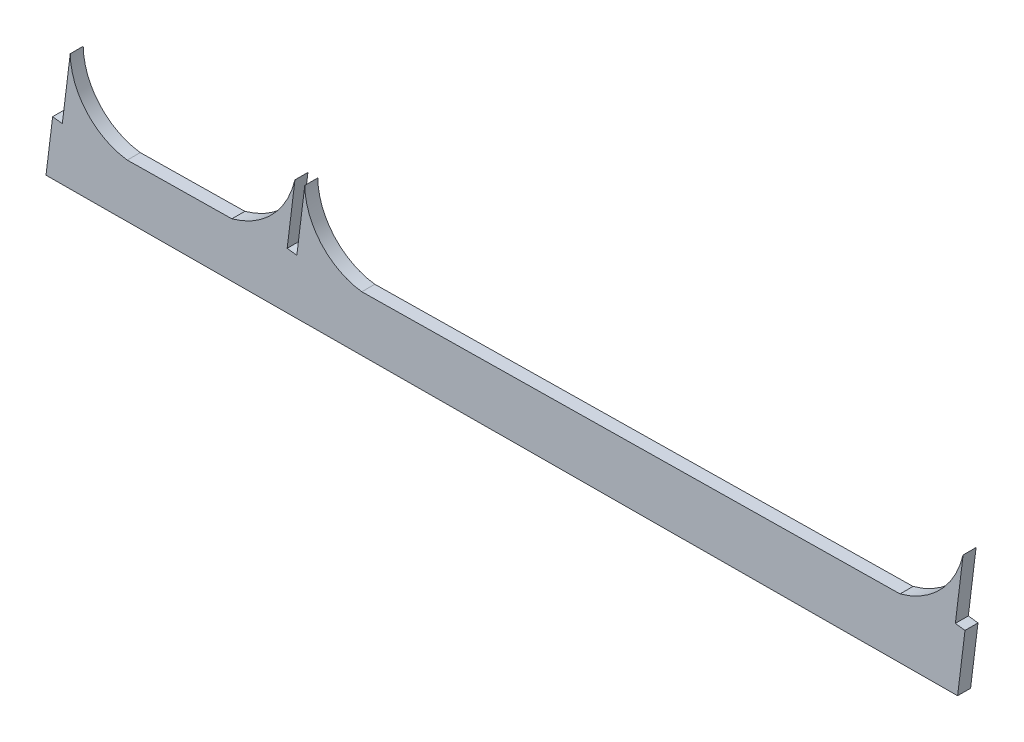
SolidWorks part; units mm, degrees
ref_plane "前视基准面" through (0, 0, 0) normal (0, 0, 1) x (1, 0, 0)
ref_plane "上视基准面" through (0, 0, 0) normal (0, 1, 0) x (1, 0, 0)
ref_plane "右视基准面" through (0, 0, 0) normal (1, 0, 0) x (0, 0, -1)
sketch "Model" plane through (0, 0, 0) normal (0, 0, 1) x (1, 0, 0)
  line L0 (13.7561, 8.5046) -> (154.0853, 9.2705)
  line L1 (16.2661, 16.6383) -> (14.7773, 16.8211)
  line L2 (52.3707, 17.1371) -> (50.8818, 17.32)
  line L3 (155.2257, 18.5582) -> (153.7369, 18.741)
  line L4 (14.7773, 16.8211) -> (13.7561, 8.5046)
  line L5 (17.4848, 26.5638) -> (16.2661, 16.6383)
  line L6 (26.2651, 16.7765) -> (42.3716, 16.999)
  line L7 (52.0755, 27.0417) -> (50.8818, 17.32)
  line L8 (53.5894, 27.0626) -> (52.3707, 17.1371)
  line L9 (62.3697, 17.2753) -> (145.2266, 18.4201)
  line L10 (154.9305, 28.4628) -> (153.7369, 18.741)
  line L11 (155.2257, 18.5582) -> (154.0853, 9.2705)
  arc A0 (17.4848, 26.5638) -> (26.2651, 16.7765) centre (27.4838, 26.7019) ccw
  arc A1 (53.5894, 27.0626) -> (62.3697, 17.2753) centre (63.5884, 27.2008) ccw
  arc A2 (42.3716, 16.999) -> (52.0755, 27.0417) centre (38.7558, 30.2024) ccw
  arc A3 (145.2266, 18.4201) -> (154.9305, 28.4628) centre (141.6108, 31.6235) ccw
extrude "凸台-拉伸1" add sketch "Model" along normal blind 2
